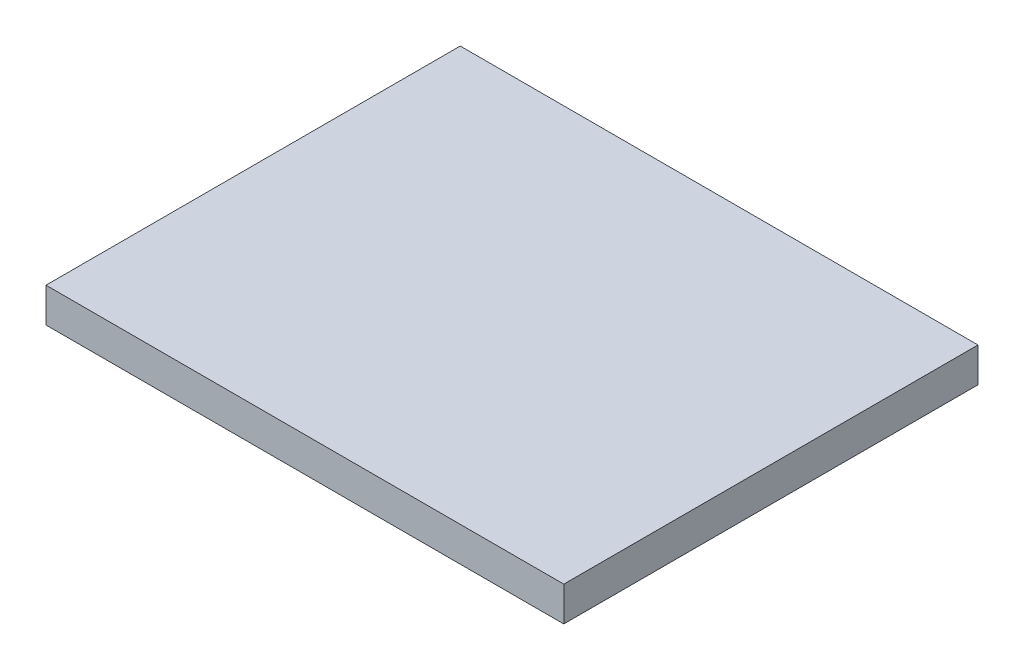
SolidWorks part; units mm, degrees
ref_plane "Front Plane" through (0, 0, 0) normal (0, 0, 1) x (1, 0, 0)
ref_plane "Top Plane" through (0, 0, 0) normal (0, 1, 0) x (1, 0, 0)
ref_plane "Right Plane" through (0, 0, 0) normal (1, 0, 0) x (0, 0, -1)
sketch "Sketch1" plane through (0, 0, 0) normal (0, 1, 0) x (1, 0, 0)
  line L1 (-47.625, 38.1) -> (47.625, 38.1)
  line L2 (-47.625, 38.1) -> (-47.625, -38.1)
  line L3 (-47.625, -38.1) -> (47.625, -38.1)
  line L4 (47.625, 38.1) -> (47.625, -38.1)
  line L5 (-47.625, 38.1) -> (47.625, -38.1) construction
  line L6 (-47.625, -38.1) -> (47.625, 38.1) construction
  point P0 (0, 0)
  dimension "D1" = 95.25
  dimension "D2" = 76.2
extrude "Boss-Extrude1" add sketch "Sketch1" along normal mid plane 6.35
